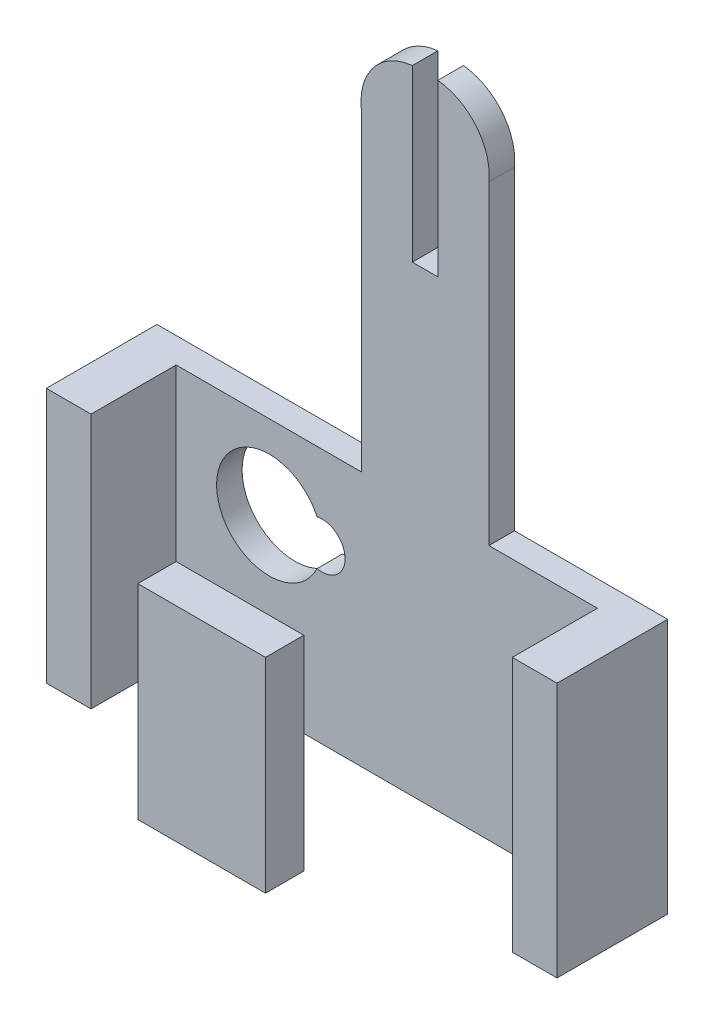
SolidWorks part; units mm, degrees
ref_plane "Front Plane" through (0, 0, 0) normal (0, 0, 1) x (1, 0, 0)
ref_plane "Top Plane" through (0, 0, 0) normal (0, 1, 0) x (1, 0, 0)
ref_plane "Right Plane" through (0, 0, 0) normal (1, 0, 0) x (0, 0, -1)
sketch "Sketch1" plane through (0, 0, 0) normal (0, 0, 1) x (1, 0, 0)
  line L0 (1.5, 0) -> (-1.5, 0)
  line L1 (-1.5, 0) -> (-1.5, 20)
  line L2 (1.5, 0) -> (1.5, 20)
  line L5 (7.5, 0) -> (7.5, 12.66)
  line L6 (-7.5, 0) -> (-7.5, 12.66)
  line L7 (-7.5, 0) -> (-7.5, -24.34)
  line L8 (7.5, 0) -> (7.5, -24.34)
  line L9 (-7.5, -24.34) -> (-34.5, -24.34)
  line L10 (-34.5, -24.34) -> (-34.5, -54.34)
  line L11 (-34.5, -54.34) -> (25.5, -54.34)
  line L12 (25.5, -54.34) -> (25.5, -24.34)
  line L13 (25.5, -24.34) -> (7.5, -24.34)
  arc A0 (-7.5, 12.66) -> (-1.5, 20) centre (-0.83, 13.33) cw
  arc A1 (1.5, 20) -> (7.5, 12.66) centre (0.83, 13.33) cw
  arc A2 (-12.6879, -31.5048) -> (-12.6879, -36.7752) centre (-18.3, -34.14) ccw
  arc A3 (-12.6879, -36.7752) -> (-12.6879, -31.5048) centre (-12.1, -34.14) ccw
  point P4 (0, 0)
  point P9 (1.5, 0)
  dimension "D13" = 6.7036
  dimension "D14" = 6.7036
  dimension "D15" = 12.4
  dimension "D16" = 5.4
  dimension "D17" = 9.8
  dimension "D18" = 16.2
  dimension "D1" = 3
  dimension "D2" = 20
  dimension "D3" = 20
  dimension "D4" = 12.66
  dimension "D5" = 12.66
  dimension "D6" = 24.34
  dimension "D7" = 24.34
  dimension "D8" = 6
  dimension "D9" = 6
  dimension "D10" = 27
  dimension "D11" = 18
  dimension "D12" = 30
extrude "Boss-Extrude1" add sketch "Sketch1" along normal blind 3
sketch "Sketch2" plane through (0, 0, 3) normal (0, 0, 1) x (1, 0, 0)
  line L0 (-34.5, -24.34) -> (-34.5, -54.34)
  line L1 (-34.5, -54.34) -> (-29.25, -54.34)
  line L2 (-34.5, -54.34) -> (25.5, -54.34) construction
  line L3 (-29.25, -54.34) -> (-29.25, -24.34)
  line L4 (-7.5, -24.34) -> (-34.5, -24.34) construction
  line L5 (-29.25, -24.34) -> (-34.5, -24.34)
  line L6 (25.5, -24.34) -> (20.25, -24.34)
  line L7 (25.5, -24.34) -> (7.5, -24.34) construction
  line L8 (20.25, -24.34) -> (20.25, -54.34)
  line L9 (20.25, -54.34) -> (25.5, -54.34)
  line L10 (25.5, -54.34) -> (25.5, -24.34) construction
  line L11 (25.5, -54.34) -> (25.5, -24.34)
  dimension "D1" = 5.25
  dimension "D2" = 5.25
extrude "Boss-Extrude2" add sketch "Sketch2" along normal blind 10
sketch "Sketch3" plane through (0, 0, 3) normal (0, 0, 1) x (1, 0, 0)
  line L0 (-29.25, -54.34) -> (-29.25, -44.34)
  line L1 (-29.25, -54.34) -> (-29.25, -24.34) construction
  line L2 (-29.25, -44.34) -> (-14.25, -44.34)
  line L3 (-14.25, -44.34) -> (-14.25, -68.34)
  line L4 (-14.25, -68.34) -> (-29.25, -68.34)
  line L5 (-29.25, -68.34) -> (-29.25, -54.34)
  dimension "D1" = 24
  dimension "D2" = 10
  dimension "D3" = 15
extrude "Boss-Extrude3" add sketch "Sketch3" along normal blind 4.5
